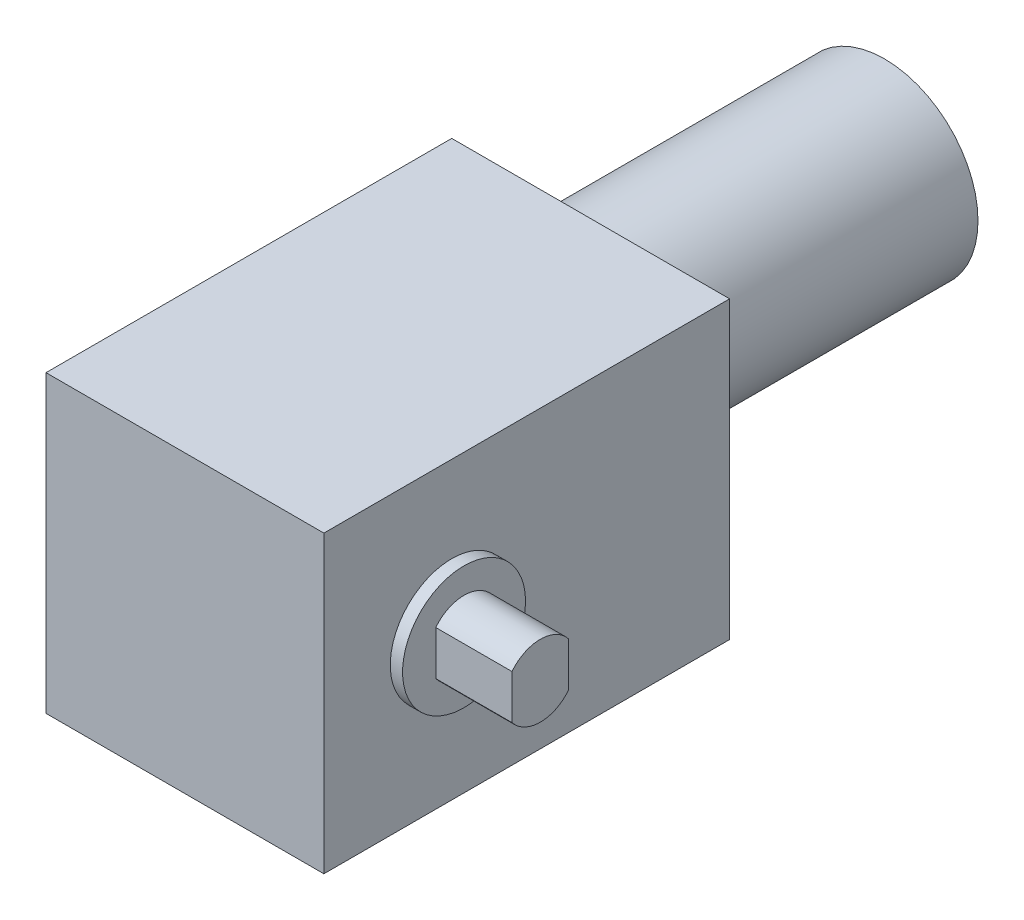
SolidWorks part; units mm, degrees
ref_plane "Front Plane" through (0, 0, 0) normal (0, 0, 1) x (1, 0, 0)
ref_plane "Top Plane" through (0, 0, 0) normal (0, 1, 0) x (1, 0, 0)
ref_plane "Right Plane" through (0, 0, 0) normal (1, 0, 0) x (0, 0, -1)
sketch "Sketch1" plane through (0, 0, 0) normal (1, 0, 0) x (0, 0, -1)
  line L1 (-5.2, 6) -> (11.3, 6)
  line L2 (-5.2, 6) -> (-5.2, -6)
  line L3 (-5.2, -6) -> (11.3, -6)
  line L4 (11.3, 6) -> (11.3, -6)
  point P4 (-5.2, 0)
  dimension "D1" = 12
  dimension "D2" = 16.5
  dimension "D3" = 5.2
extrude "Base" add sketch "Sketch1" against normal blind 11.3
sketch "Sketch2" plane through (0, 0, 0) normal (1, 0, 0) x (0, 0, -1)
  circle A0 centre (0, 0) radius 2.5
  dimension "D1" = 5
extrude "Axle Base" add sketch "Sketch2" along normal blind 0.5
sketch "Sketch3" plane through (0.5, 0, 0) normal (1, 0, 0) x (0, 0, -1)
  line L0 (1.15, 0.8995) -> (1.15, -0.8995)
  line L1 (-1.15, 0.8995) -> (-1.15, -0.8995)
  line L3 (-1.15, 0) -> (1.15, 0) construction
  arc A0 (1.15, 0.8995) -> (-1.15, 0.8995) centre (0, 0) ccw
  arc A1 (-1.15, -0.8995) -> (1.15, -0.8995) centre (0, 0) ccw
  point P11 (0, 0)
  dimension "D1" = 2.92
  dimension "D2" = 2.3
extrude "Axle" add sketch "Sketch3" along normal blind 3.1
sketch "Sketch4" plane through (0, 0, -11.3) normal (0, 0, -1) x (-1, 0, 0)
  line L1 (11.3, -6) -> (11.3, 6) construction
  circle A0 centre (7.5, 0) radius 3.8
  dimension "D1" = 7.6
extrude "Wire Housing" add sketch "Sketch4" along normal blind 13.8
sketch "Sketch5" plane through (-11.3, 0, 0) normal (-1, 0, 0) x (0, 0, 1)
  line L0 (5.2, 6) -> (5.2, -6) construction
  circle A0 centre (-5.3, 0) radius 1.25
  dimension "D1" = 2.5
  dimension "D2" = 10.5
extrude "Random-ass Bump" add sketch "Sketch5" along normal blind 0.4
